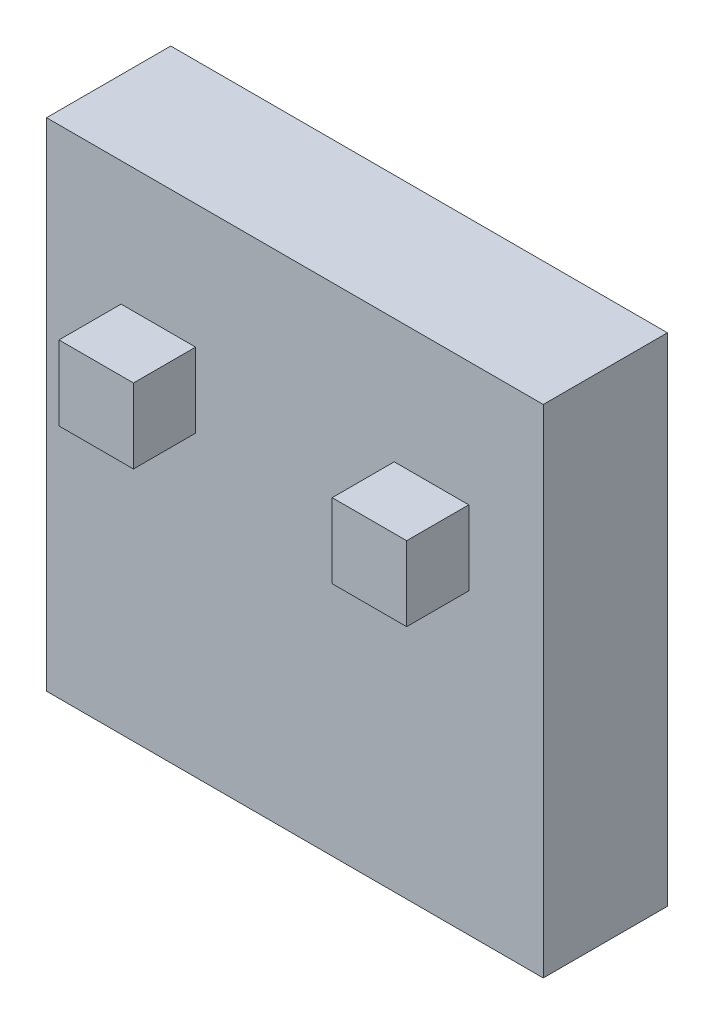
SolidWorks part; units mm, degrees
ref_plane "Front Plane" through (0, 0, 0) normal (0, 0, 1) x (1, 0, 0)
ref_plane "Top Plane" through (0, 0, 0) normal (0, 1, 0) x (1, 0, 0)
ref_plane "Right Plane" through (0, 0, 0) normal (1, 0, 0) x (0, 0, -1)
sketch "Sketch1" plane through (0, 0, 0) normal (0, 0, 1) x (1, 0, 0)
  line L1 (-20, 0) -> (20, 0)
  line L2 (-20, 0) -> (-20, 40)
  line L3 (-20, 40) -> (20, 40)
  line L4 (20, 0) -> (20, 40)
extrude "Boss-Extrude1" add sketch "Sketch1" along normal blind 10
sketch "Sketch2" plane through (0, 0, 0) normal (0, 0, 1) x (1, 0, 0)
  line L1 (-14, 8) -> (-8, 8)
  line L2 (-14, 8) -> (-14, 14)
  line L3 (-14, 14) -> (-8, 14)
  line L4 (-8, 8) -> (-8, 14)
extrude "Cut-Extrude1" cut sketch "Sketch2" along normal blind 5
ref_plane "Plane1" through (0, 0, 10) normal (0, 0, 1) x (1, 0, 0)
sketch "Sketch3" plane through (0, 0, 10) normal (0, 0, 1) x (1, 0, 0)
  line L1 (-14, 24) -> (-8, 24)
  line L2 (-14, 24) -> (-14, 30)
  line L3 (-14, 30) -> (-8, 30)
  line L4 (-8, 24) -> (-8, 30)
extrude "Boss-Extrude2" add sketch "Sketch3" along normal blind 5
mirror "Mirror1" about plane through (0, 0, 0) normal (1, 0, 0) of "Boss-Extrude2", "Cut-Extrude1"
